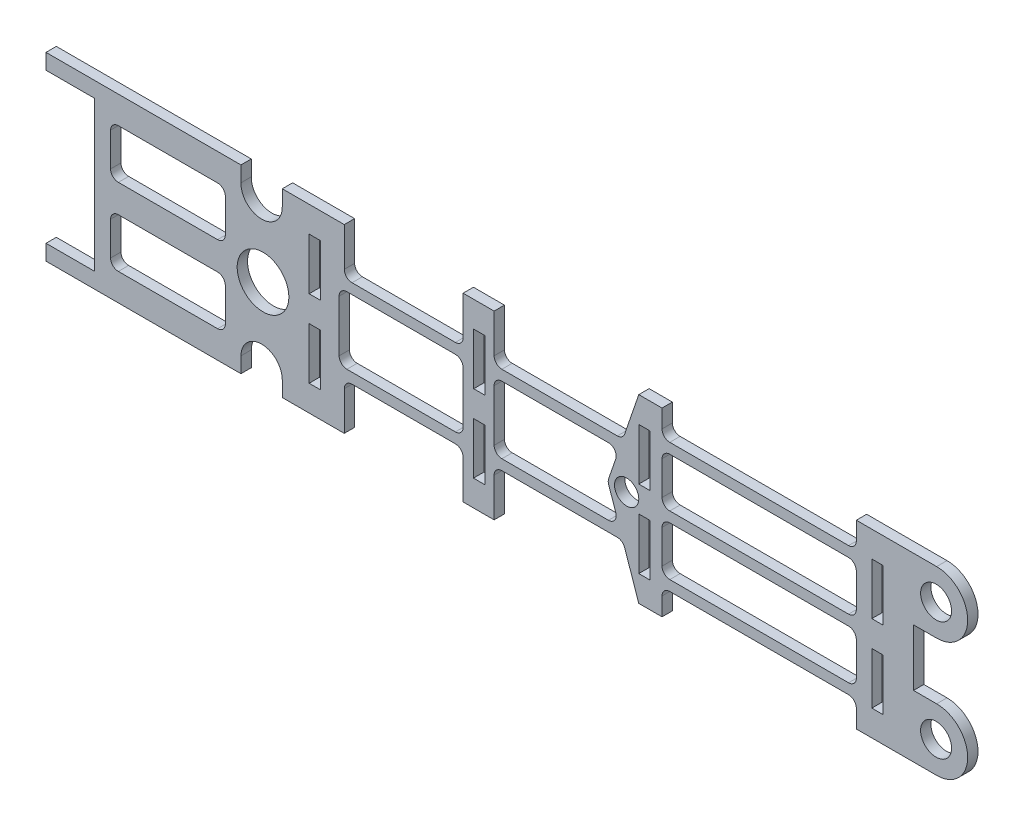
SolidWorks part; units mm, degrees
ref_plane "前视基准面" through (0, 0, 0) normal (0, 0, 1) x (1, 0, 0)
ref_plane "上视基准面" through (0, 0, 0) normal (0, 1, 0) x (1, 0, 0)
ref_plane "右视基准面" through (0, 0, 0) normal (1, 0, 0) x (0, 0, -1)
sketch "Model" plane through (0, 0, 0) normal (0, 0, 1) x (1, 0, 0)
  line L0 (161.306, 22.5857) -> (161.306, 29.0857)
  line L1 (159.806, 30.5857) -> (125.206, 30.5857)
  line L2 (123.706, 29.0857) -> (123.706, 22.5857)
  line L3 (125.206, 21.0857) -> (159.806, 21.0857)
  line L4 (123.706, 17.5857) -> (123.706, 11.0857)
  line L5 (125.206, 9.5857) -> (159.806, 9.5857)
  line L6 (161.306, 11.0857) -> (161.306, 17.5857)
  line L7 (159.806, 19.0857) -> (125.206, 19.0857)
  line L8 (55.4068, 7.5857) -> (57.6068, 7.5857)
  line L9 (57.6068, 7.5857) -> (57.6068, 17.5857)
  line L10 (57.6068, 17.5857) -> (55.4068, 17.5857)
  line L11 (55.4068, 17.5857) -> (55.4068, 7.5857)
  line L12 (55.4068, 32.5857) -> (57.6068, 32.5857)
  line L13 (57.6068, 32.5857) -> (57.6068, 22.5857)
  line L14 (57.6068, 22.5857) -> (55.4068, 22.5857)
  line L15 (55.4068, 22.5857) -> (55.4068, 32.5857)
  line L16 (166.506, 17.5857) -> (164.306, 17.5857)
  line L17 (164.306, 17.5857) -> (164.306, 7.5857)
  line L18 (164.306, 7.5857) -> (166.506, 7.5857)
  line L19 (166.506, 7.5857) -> (166.506, 17.5857)
  line L20 (166.506, 32.5857) -> (166.506, 22.5857)
  line L21 (166.506, 22.5857) -> (164.306, 22.5857)
  line L22 (164.306, 22.5857) -> (164.306, 32.5857)
  line L23 (164.306, 32.5857) -> (166.506, 32.5857)
  line L24 (119.2066, 7.5857) -> (121.4066, 7.5857)
  line L25 (121.4066, 7.5857) -> (121.4066, 17.5857)
  line L26 (121.4066, 17.5857) -> (119.2066, 17.5857)
  line L27 (119.2066, 17.5857) -> (119.2066, 7.5857)
  line L28 (119.2066, 32.5857) -> (121.4066, 32.5857)
  line L29 (121.4066, 32.5857) -> (121.4066, 22.5857)
  line L30 (121.4066, 22.5857) -> (119.2066, 22.5857)
  line L31 (119.2066, 22.5857) -> (119.2066, 32.5857)
  line L32 (87.2068, 7.5857) -> (89.4068, 7.5857)
  line L33 (89.4068, 7.5857) -> (89.4068, 17.5834)
  line L34 (89.4068, 17.5834) -> (87.2068, 17.5857)
  line L35 (87.2068, 17.5857) -> (87.2068, 7.5857)
  line L36 (87.2534, 32.591) -> (89.4534, 32.591)
  line L37 (89.4534, 32.591) -> (89.4067, 22.591)
  line L38 (89.4067, 22.591) -> (87.2534, 22.591)
  line L39 (87.2534, 22.591) -> (87.2534, 32.591)
  line L40 (62.7068, 13.5857) -> (83.7068, 13.5857)
  line L41 (85.2068, 15.0857) -> (85.2068, 25.0857)
  line L42 (83.7068, 26.5857) -> (62.7068, 26.5857)
  line L43 (61.2068, 25.0857) -> (61.2068, 15.0857)
  line L44 (113.3352, 26.5857) -> (92.7068, 26.5857)
  line L45 (91.2068, 25.0857) -> (91.2068, 15.0857)
  line L46 (92.7068, 13.5857) -> (113.3352, 13.5857)
  line L47 (114.7541, 15.5722) -> (113.3734, 19.5992)
  line L48 (113.3734, 20.5722) -> (114.7541, 24.5992)
  line L49 (42.2078, 34.5857) -> (42.2078, 37.5857)
  line L50 (62.2068, 2.5857) -> (62.2068, 10.0857)
  line L51 (63.7068, 11.5857) -> (83.7068, 11.5857)
  line L52 (85.2068, 10.0857) -> (85.2068, 2.5857)
  line L53 (85.2068, 2.5857) -> (91.2068, 2.5857)
  line L54 (91.2068, 2.5857) -> (91.2068, 10.0857)
  line L55 (92.7068, 11.5857) -> (115.0495, 11.5857)
  line L56 (116.4684, 10.5722) -> (119.2066, 2.5857)
  line L57 (119.2066, 2.5857) -> (123.706, 2.5857)
  line L58 (123.706, 2.5857) -> (123.706, 6.0857)
  line L59 (125.206, 7.5857) -> (159.806, 7.5857)
  line L60 (161.306, 6.0857) -> (161.306, 2.5857)
  line L61 (161.306, 2.5857) -> (176.8579, 2.5857)
  line L62 (176.8579, 14.5857) -> (172.376, 14.5857)
  line L63 (172.376, 14.5857) -> (172.376, 25.5857)
  line L64 (172.376, 25.5857) -> (176.8579, 25.5857)
  line L65 (176.8579, 37.5857) -> (161.306, 37.5857)
  line L66 (161.306, 37.5857) -> (161.306, 34.0857)
  line L67 (159.806, 32.5857) -> (125.206, 32.5857)
  line L68 (123.706, 34.0857) -> (123.706, 37.5857)
  line L69 (123.706, 37.5857) -> (119.2066, 37.5857)
  line L70 (119.2066, 37.5857) -> (116.4684, 29.5992)
  line L71 (115.0495, 28.5857) -> (92.7068, 28.5857)
  line L72 (91.2068, 30.0857) -> (91.2068, 37.5857)
  line L73 (91.2068, 37.5857) -> (85.2068, 37.5857)
  line L74 (85.2068, 37.5857) -> (85.2068, 30.0857)
  line L75 (83.7068, 28.5857) -> (63.7068, 28.5857)
  line L76 (62.2068, 30.0857) -> (62.2068, 37.5857)
  line L77 (62.2068, 37.5857) -> (50.2058, 37.5857)
  line L78 (50.2058, 37.5857) -> (50.2058, 34.5857)
  line L79 (42.2078, 37.5857) -> (4.4782, 37.5857)
  line L80 (42.2078, 5.5857) -> (42.2078, 2.5857)
  line L81 (62.2068, 2.5857) -> (50.2058, 2.5857)
  line L82 (50.2058, 2.5857) -> (50.2073, 5.5185)
  line L83 (42.2078, 2.5857) -> (4.4782, 2.5857)
  line L84 (4.4782, 37.5857) -> (4.4782, 34.5857)
  line L85 (13.8782, 34.5857) -> (13.8782, 5.5857)
  line L86 (4.4782, 5.5857) -> (4.4782, 2.5857)
  line L87 (4.4782, 34.5857) -> (13.8782, 34.5857)
  line L88 (4.4782, 5.5857) -> (13.8782, 5.5857)
  line L89 (18.478, 22.7993) -> (37.6819, 22.7993)
  line L90 (39.1819, 24.2993) -> (39.1819, 30.7993)
  line L91 (37.6819, 32.2993) -> (18.478, 32.2993)
  line L92 (16.978, 30.7993) -> (16.978, 24.2993)
  line L93 (18.478, 17.3721) -> (37.6819, 17.3721)
  line L94 (39.1819, 15.8721) -> (39.1819, 9.3721)
  line L95 (37.6819, 7.8721) -> (18.478, 7.8721)
  line L96 (16.978, 9.3721) -> (16.978, 15.8721)
  circle A0 centre (176.7453, 8.5857) radius 3
  circle A1 centre (176.7453, 31.5857) radius 3
  circle A2 centre (116.8566, 20.0857) radius 2.35
  circle A3 centre (46.4799, 20.0857) radius 5
  arc A4 (61.2068, 15.0857) -> (62.7068, 13.5857) centre (62.7068, 15.0857) ccw
  arc A5 (83.7068, 13.5857) -> (85.2068, 15.0857) centre (83.7068, 15.0857) ccw
  arc A6 (85.2068, 25.0857) -> (83.7068, 26.5857) centre (83.7068, 25.0857) ccw
  arc A7 (62.7068, 26.5857) -> (61.2068, 25.0857) centre (62.7068, 25.0857) ccw
  arc A8 (42.2078, 34.5857) -> (50.2058, 34.5857) centre (46.2068, 34.5014) ccw
  arc A9 (63.7068, 11.5857) -> (62.2068, 10.0857) centre (63.7068, 10.0857) ccw
  arc A10 (85.2068, 10.0857) -> (83.7068, 11.5857) centre (83.7068, 10.0857) ccw
  arc A11 (92.7068, 11.5857) -> (91.2068, 10.0857) centre (92.7068, 10.0857) ccw
  arc A12 (116.4684, 10.5722) -> (115.0495, 11.5857) centre (115.0495, 10.0857) ccw
  arc A13 (125.206, 7.5857) -> (123.706, 6.0857) centre (125.206, 6.0857) ccw
  arc A14 (161.306, 6.0857) -> (159.806, 7.5857) centre (159.806, 6.0857) ccw
  arc A15 (176.8579, 2.5857) -> (176.8579, 14.5857) centre (176.8579, 8.5857) ccw
  arc A16 (176.8579, 25.5857) -> (176.8579, 37.5857) centre (176.8579, 31.5857) ccw
  arc A17 (159.806, 32.5857) -> (161.306, 34.0857) centre (159.806, 34.0857) ccw
  arc A18 (123.706, 34.0857) -> (125.206, 32.5857) centre (125.206, 34.0857) ccw
  arc A19 (115.0495, 28.5857) -> (116.4684, 29.5992) centre (115.0495, 30.0857) ccw
  arc A20 (91.2068, 30.0857) -> (92.7068, 28.5857) centre (92.7068, 30.0857) ccw
  arc A21 (83.7068, 28.5857) -> (85.2068, 30.0857) centre (83.7068, 30.0857) ccw
  arc A22 (62.2068, 30.0857) -> (63.7068, 28.5857) centre (63.7068, 30.0857) ccw
  arc A23 (50.2073, 5.5185) -> (42.2078, 5.5857) centre (46.2076, 5.5521) ccw
  arc A24 (16.978, 24.2993) -> (18.478, 22.7993) centre (18.478, 24.2993) ccw
  arc A25 (37.6819, 22.7993) -> (39.1819, 24.2993) centre (37.6819, 24.2993) ccw
  arc A26 (39.1819, 30.7993) -> (37.6819, 32.2993) centre (37.6819, 30.7993) ccw
  arc A27 (18.478, 32.2993) -> (16.978, 30.7993) centre (18.478, 30.7993) ccw
  arc A28 (18.478, 17.3721) -> (16.978, 15.8721) centre (18.478, 15.8721) ccw
  arc A29 (39.1819, 15.8721) -> (37.6819, 17.3721) centre (37.6819, 15.8721) ccw
  arc A30 (37.6819, 7.8721) -> (39.1819, 9.3721) centre (37.6819, 9.3721) ccw
  arc A31 (16.978, 9.3721) -> (18.478, 7.8721) centre (18.478, 9.3721) ccw
  arc A32 (161.306, 29.0857) -> (159.806, 30.5857) centre (159.806, 29.0857) ccw
  arc A33 (125.206, 30.5857) -> (123.706, 29.0857) centre (125.206, 29.0857) ccw
  arc A34 (123.706, 22.5857) -> (125.206, 21.0857) centre (125.206, 22.5857) ccw
  arc A35 (159.806, 21.0857) -> (161.306, 22.5857) centre (159.806, 22.5857) ccw
  arc A36 (123.706, 11.0857) -> (125.206, 9.5857) centre (125.206, 11.0857) ccw
  arc A37 (159.806, 9.5857) -> (161.306, 11.0857) centre (159.806, 11.0857) ccw
  arc A38 (161.306, 17.5857) -> (159.806, 19.0857) centre (159.806, 17.5857) ccw
  arc A39 (125.206, 19.0857) -> (123.706, 17.5857) centre (125.206, 17.5857) ccw
  arc A40 (114.7541, 24.5992) -> (113.3352, 26.5857) centre (113.3352, 25.0857) ccw
  arc A41 (92.7068, 26.5857) -> (91.2068, 25.0857) centre (92.7068, 25.0857) ccw
  arc A42 (91.2068, 15.0857) -> (92.7068, 13.5857) centre (92.7068, 15.0857) ccw
  arc A43 (113.3352, 13.5857) -> (114.7541, 15.5722) centre (113.3352, 15.0857) ccw
  arc A44 (113.3734, 20.5722) -> (113.3734, 19.5992) centre (114.7924, 20.0857) ccw
  point P22 (0, 0)
  point P189 (0, 0)
extrude "凸台-拉伸1" add sketch "Model" along normal blind 2
